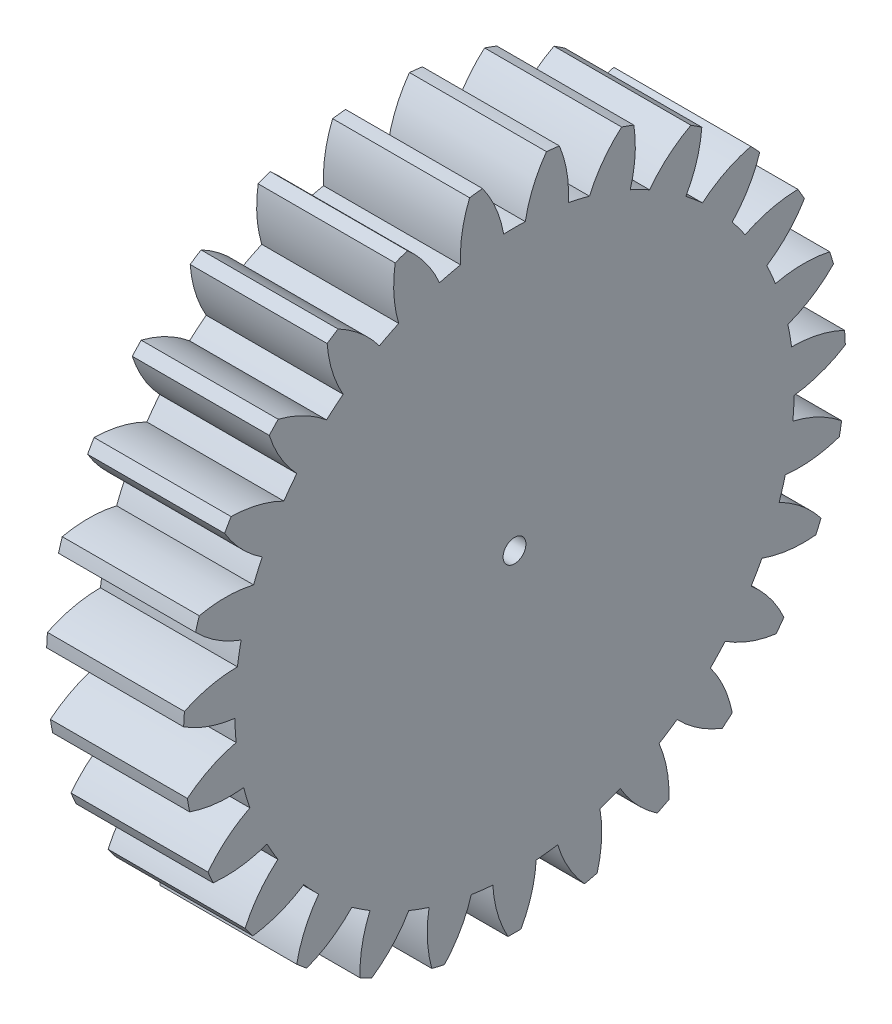
SolidWorks part; units mm, degrees
ref_plane "Plane1" through (0, 0, 0) normal (0, 0, 1) x (1, 0, 0)
ref_plane "Plane2" through (0, 0, 0) normal (0, 1, 0) x (1, 0, 0)
ref_plane "Plane3" through (0, 0, 0) normal (1, 0, 0) x (0, 0, -1)
other "Configuration Table"
sketch "HoldingSke" plane through (0, 0, 0) normal (0, 1, 0) x (1, 0, 0)
  line L0 (0, 0) -> (0.891, -0.454)
  line L1 (-15, 0) -> (100, 0) construction
  line L2 (0, 0) -> (-2.1039, 2.3779)
  line L3 (0, 0) -> (-11.863, 4.5341)
  line L4 (0, 0) -> (7.6947, 3.9207)
  line L5 (0, 0) -> (-46.8476, -17.4728)
  line L6 (0, 0) -> (-4.9738, -3.3558)
  line L7 (-2.1039, 2.3779) -> (8.6586, 51.2059)
  line L8 (-76.2, 54.61) -> (-76.1, 54.61)
  line L9 (-71.009, 38.7566) -> (-53.1078, 45.2721)
  line L10 (-76.2, 71.12) -> (104.1128, 71.12)
  line L11 (0, 0) -> (-6, 0)
  line L12 (-76.2, 101.6) -> (-76.162, 101.6)
  line L13 (24.9733, 27.94) -> (52.9518, 28.4284)
  line L14 (24.9733, 27.94) -> (24.9743, 27.94)
  line L15 (24.9733, 27.94) -> (100.4006, 29.5858)
  line L16 (-63.627, -1) -> (-12.827, -1)
  circle A0 centre (0, 0) radius 0.5
  circle A1 centre (0, 0) radius 12.249
  circle A2 centre (0, 0) radius 37.5
  circle A3 centre (0, 0) radius 0.5
  dimension "MHD" = 24.498
  dimension "Hub_dia" = 75
  dimension "Bore" = 1
  dimension "MBD" = 1
  dimension "Num_teeth" = 27
  dimension "Pitch" = 1
  dimension "Overall_len" = 50
  dimension "Show_teeth" = 27
  dimension "Thickness" = 6
  dimension "OAL" = 50.0001
  dimension "T_dim" = 0.1
  dimension "Ap" = 20
  dimension "H" = 19.05
  dimension "Pitch_radius" = 180.3128
  dimension "Width" = 6
  dimension "Backlash" = 0.038
  dimension "Addendum_fac" = 1
  dimension "Dedendum_fac" = 1.25
  dimension "Clearance_fac" = 0.25
  dimension "Dedendum_add" = 0.001
  dimension "Module" = 1
sketch "BasProSke" plane through (0, 0, 0) normal (0, 1, 0) x (1, 0, 0)
  line L0 (-10, 0) -> (60, 0) construction
  line L1 (0, 0) -> (0, 14.5)
  line L2 (0, 0) -> (6, 0)
  line L3 (6, 0) -> (6, 14.5)
  line L4 (6, 14.5) -> (0, 14.5)
  dimension "Thickness" = 6
  dimension "Diameter" = 29
revolve "Base-Revolve" add sketch "BasProSke" angle 360 about L0
sketch "TooCutSke" plane through (0, 0, 0) normal (1, 0, 0) x (0, 0, -1)
  line L1 (0, 0) -> (0, 107) construction
  line L2 (0, 0) -> (-0.8514, 13.4731) construction
  line L3 (0, 0) -> (-3.1301, 26.7794) construction
  line L4 (-0.8514, 13.4731) -> (-1.565, 13.3897) construction
  arc A0 (0.4741, 12.2398) -> (-0.4741, 12.2398) centre (0, 0) ccw
  arc A1 (1.4167, 14.4561) -> (-1.4167, 14.4561) centre (0, 0) ccw
  circle A2 centre (0, 0) radius 13.5 construction
  circle A3 centre (0, 0) radius 12.6859 construction
  arc A4 (-0.4741, 12.2398) -> (-1.4167, 14.4561) centre (-5.7895, 11.2877) ccw
  arc A5 (1.4167, 14.4561) -> (0.4741, 12.2398) centre (5.7895, 11.2877) ccw
  dimension "Root_dia" = 24.498
  dimension "Overcut_dia" = 29.0508
  dimension "Pitch_dia" = 27
  dimension "Base_dia" = 25.3717
  dimension "Flank_rad" = 5.4
  dimension "Half_ang" = 6.667
  dimension "Half_CT" = 0.7185
extrude "ToothCut" cut sketch "TooCutSke" along normal through all
fillet "Breaks" [suppressed] radius 0.02
fillet "RootFillets" [suppressed] radius 0.251
pattern_circular "TeethCuts" count 27 every 13.333 about axis through (-10, 0, 0) along (1, 0, 0) of "ToothCut", "RootFillets", "Breaks"
sketch "HubNeaOneSke" plane through (0, 0, 0) normal (-1, 0, 0) x (0, 0, 1)
  circle A0 centre (0, 0) radius 12.249
  dimension "Diameter" = 24.498
extrude "HubNearOne" [suppressed] add sketch "HubNeaOneSke" along normal blind 44.0001
sketch "HubNeaBotSke" plane through (0, 0, 0) normal (-1, 0, 0) x (0, 0, 1)
  circle A0 centre (0, 0) radius 12.249
  dimension "Diameter" = 24.498
extrude "HubNearBoth" [suppressed] add sketch "HubNeaBotSke" along normal blind 22
ref_plane "FarPln" through (6, 0, 0) normal (1, 0, 0) x (0, 0, -1)
sketch "HubFarSke" plane through (6, 0, 0) normal (1, 0, 0) x (0, 0, -1)
  circle A0 centre (0, 0) radius 12.249
  dimension "Diameter" = 24.498
extrude "HubFar" [suppressed] add sketch "HubFarSke" along normal blind 22
sketch "BorSke" plane through (0, 0, 0) normal (1, 0, 0) x (0, 0, -1)
  circle A0 centre (0, 0) radius 0.5
  dimension "Diameter" = 1
extrude "Bore" cut sketch "BorSke" along normal mid plane 100.0001
sketch "KeySke" plane through (0, 0, 0) normal (1, 0, 0) x (0, 0, -1)
  line L0 (-0.05, 0) -> (-0.05, 0.6)
  line L1 (-0.05, 0.6) -> (0.05, 0.6)
  line L2 (0.05, 0.6) -> (0.05, 0)
  line L3 (0, 0) -> (0, 34) construction
  line L4 (-0.05, 0) -> (0.05, 0)
  dimension "Offset" = 0.6
  dimension "Width" = 0.1
extrude "Keyway" [suppressed] cut sketch "KeySke" along normal mid plane 100.0001
pattern_circular "Keyway2" [suppressed] count 2 every 90 about axis through (-10, 0, 0) along (1, 0, 0)
equation "' \"Module@HoldingSke\" = 6.35"
equation "' \"Num_teeth@HoldingSke\" = 12"
equation "' \"Ap@HoldingSke\" =  20"
equation "' \"Ap@HoldingSke\" = 20"
equation "' \"Width@HoldingSke\" = 0.5 * 25.4"
equation "' \"Hub_dia@HoldingSke\"= 1 * 25.4"
equation "' \"Hub_dia@HoldingSke\" = 1 * 25.4"
equation "' \"Overall_len@HoldingSke\" = 1.0 * 25.4"
equation "' \"Bore@HoldingSke\" = 0.75 * 25.4"
equation "' \"T_dim@HoldingSke\" = 0.1 * 25.4"
equation "' \"Width@KeySke\" = 0.25 * 25.4"
equation "' \"Show_teeth@HoldingSke\" = 13"
equation "' \"Backlash@HoldingSke\" = 0.009 * 25.4"
equation "' \"Addendum_fac@HoldingSke\" = 1.0"
equation "' \"Dedendum_fac@HoldingSke\" = 1.25"
equation "' \"Dedendum_add@HoldingSke\" = 0.00005 * 25.4"
equation "' \"Clearance_fac@HoldingSke\" = 0.25"
equation "\"Pitch@HoldingSke\" = 1 / \"Module@HoldingSke\""
equation "\"Overcut_dia@TooCutSke\" = (\"Num_teeth@HoldingSke\" + 2 * \"Addendum_fac@HoldingSke\") / \"Pitch@HoldingSke\" + 0.002 * 25.4"
equation "\"Pitch_dia@TooCutSke\" = \"Num_teeth@HoldingSke\" / \"Pitch@HoldingSke\""
equation "\"Base_dia@TooCutSke\" = \"Num_teeth@HoldingSke\" / \"Pitch@HoldingSke\" * cos((\"Ap@HoldingSke\"  * 3.14159265 / 180))"
equation "\"Root_dia@TooCutSke\" = (\"Num_teeth@HoldingSke\" + 2) / \"Pitch@HoldingSke\" - 2 * (\"Addendum_fac@HoldingSke\" + \"Dedendum_fac@HoldingSke\") / \"Pitch@HoldingSke\" - \"Dedendum_add@HoldingSke\" * 2"
equation "\"Half_ang@TooCutSke\" = 180 / \"Num_teeth@HoldingSke\""
equation "\"Half_CT@TooCutSke\" = \"Num_teeth@HoldingSke\" / \"Pitch@HoldingSke\" * sin((3.14159265 / 2 / \"Num_teeth@HoldingSke\")) / 2 - 7 * \"Backlash@HoldingSke\" / 4"
equation "\"Flank_rad@TooCutSke\" = \"Num_teeth@HoldingSke\" / \"Pitch@HoldingSke\" / 5"
equation "\"Radius@RootFillets\" = \"Clearance_fac@HoldingSke\" / \"Pitch@HoldingSke\" + \"Dedendum_add@HoldingSke\""
equation "\"Break_rad@Breaks\" = 0.02 / \"Pitch@HoldingSke\""
equation "\"Thickness@HoldingSke\" = \"Width@HoldingSke\""
equation "\"OAL@HoldingSke\" = \"Thickness@HoldingSke\""
equation "\"MHD@HoldingSke\" = (\"Num_teeth@HoldingSke\" + 2) / \"Pitch@HoldingSke\" - 2 * (\"Addendum_fac@HoldingSke\" + \"Dedendum_fac@HoldingSke\")  / \"Pitch@HoldingSke\" - \"Dedendum_add@HoldingSke\" * 2"
equation "\"MBD@HoldingSke\" = (\"Num_teeth@HoldingSke\" + 2) / \"Pitch@HoldingSke\" - 2 * (\"Addendum_fac@HoldingSke\" + \"Dedendum_fac@HoldingSke\")  / \"Pitch@HoldingSke\" - \"Dedendum_add@HoldingSke\" * 2 - 0.002 * 25.4"
equation "\"MHD@HoldingSke\" = ((sgn( \"MHD@HoldingSke\" - \"Hub_dia@HoldingSke\" )-1)*( \"MHD@HoldingSke\" - \"Hub_dia@HoldingSke\" ))/-2+ \"Hub_dia@HoldingSke\""
equation "\"MBD@HoldingSke\" = ((sgn( \"MBD@HoldingSke\" - \"Bore@HoldingSke\" )-1)*( \"MBD@HoldingSke\" - \"Bore@HoldingSke\" ))/-2+ \"Bore@HoldingSke\""
equation "\"OAL@HoldingSke\" = ((sgn( \"OAL@HoldingSke\" - \"Overall_len@HoldingSke\" )+1)*( \"OAL@HoldingSke\" - \"Overall_len@HoldingSke\" ))/2 + \"Overall_len@HoldingSke\" + 0.000002 * 25.4"
equation "\"Num_teeth@TeethCuts\" = int( \"Show_teeth@HoldingSke\" ) + 1"
equation "\"Num_teeth@TeethCuts\" = ((sgn( \"Num_teeth@TeethCuts\" - \"Num_teeth@HoldingSke\" )-1)*( \"Num_teeth@TeethCuts\" - \"Num_teeth@HoldingSke\" ))/-2+ \"Num_teeth@HoldingSke\""
equation "\"Num_teeth@TeethCuts\" = ((sgn( \"Num_teeth@TeethCuts\" - 2.0)+1)*( \"Num_teeth@TeethCuts\" - 2.0))/2 +2.0"
equation "\"Angle@TeethCuts\" = 360.0 / \"Num_teeth@HoldingSke\""
equation "\"Diameter@BasProSke\" = (\"Num_teeth@HoldingSke\" + 2 * \"Addendum_fac@HoldingSke\") / \"Pitch@HoldingSke\""
equation "\"Thickness@BasProSke\"  = \"Thickness@HoldingSke\""
equation "' \"Fillet_rad@BasProSke\" =  \"Thickness@HoldingSke\" * 0.05"
equation "' \"Fillet_rad@BasProSke\" = \"Thickness@HoldingSke\" * 0.05"
equation "\"MHD@HoldingSke\" = ((sgn( \"MHD@HoldingSke\" - \"Root_dia@TooCutSke\" )-1)*( \"MHD@HoldingSke\" - \"Root_dia@TooCutSke\" ))/-2+ \"Root_dia@TooCutSke\""
equation "\"Diameter@HubNeaOneSke\" = \"MHD@HoldingSke\""
equation "\"Length@HubNearOne\" = \"OAL@HoldingSke\" - \"Thickness@BasProSke\""
equation "\"Diameter@HubNeaBotSke\" = \"MHD@HoldingSke\""
equation "\"Length@HubNearBoth\" = ( \"OAL@HoldingSke\" - \"Thickness@BasProSke\" ) / 2.0"
equation "\"Thickness@FarPln\" = \"Thickness@BasProSke\""
equation "\"Diameter@HubFarSke\" = \"MHD@HoldingSke\""
equation "\"Length@HubFar\" = ( \"OAL@HoldingSke\" - \"Thickness@BasProSke\" ) / 2.0"
equation "\"Diameter@BorSke\" = \"MBD@HoldingSke\""
equation "\"D1@Bore\" = \"OAL@HoldingSke\" * 2.0"
equation "\"D1@Keyway\" = \"OAL@HoldingSke\" * 2.0"
equation "\"Offset@KeySke\" = \"T_dim@HoldingSke\" + \"MBD@HoldingSke\" / 2.0"
